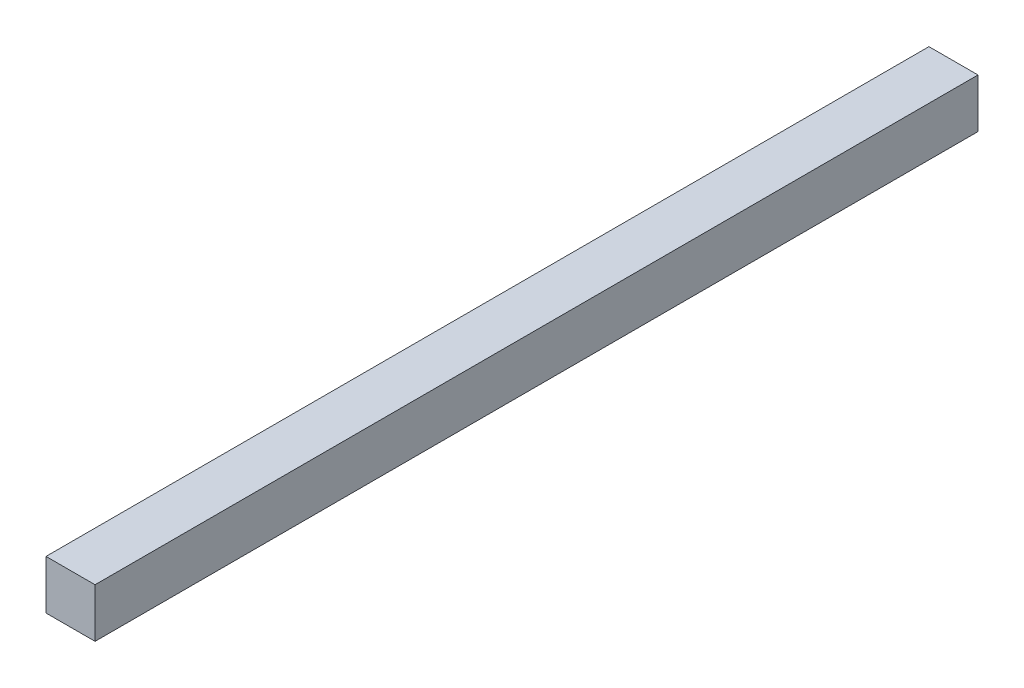
SolidWorks part; units mm, degrees
ref_plane "Front Plane" through (0, 0, 0) normal (0, 0, 1) x (1, 0, 0)
ref_plane "Top Plane" through (0, 0, 0) normal (0, 1, 0) x (1, 0, 0)
ref_plane "Right Plane" through (0, 0, 0) normal (1, 0, 0) x (0, 0, -1)
sketch "Sketch1" plane through (0, 0, 0) normal (0, 0, 1) x (1, 0, 0)
  line L1 (0, 0) -> (-25.4, 0)
  line L2 (0, 0) -> (0, -25.4)
  line L3 (0, -25.4) -> (-25.4, -25.4)
  line L4 (-25.4, 0) -> (-25.4, -25.4)
  dimension "D1" = 25.4
  dimension "D2" = 25.4
extrude "Boss-Extrude1" add sketch "Sketch1" along normal blind 457.2 contours L1 L4 L3 L2
